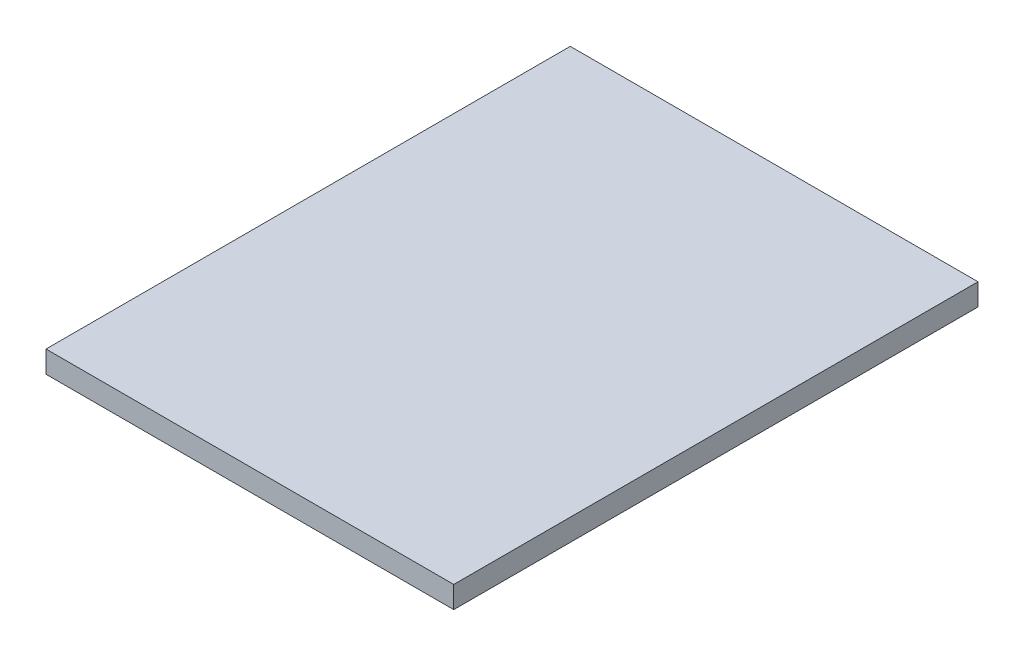
SolidWorks part; units mm, degrees
material "Acrylic (Medium-high impact)"
ref_plane "Front Plane" through (0, 0, 0) normal (0, 0, 1) x (1, 0, 0)
ref_plane "Top Plane" through (0, 0, 0) normal (0, 1, 0) x (1, 0, 0)
ref_plane "Right Plane" through (0, 0, 0) normal (1, 0, 0) x (0, 0, -1)
sketch "Sketch1" plane through (0, 0, 0) normal (0, 1, 0) x (1, 0, 0)
  line L1 (-88.9, 114.3) -> (88.9, 114.3)
  line L2 (-88.9, 114.3) -> (-88.9, -114.3)
  line L3 (-88.9, -114.3) -> (88.9, -114.3)
  line L4 (88.9, 114.3) -> (88.9, -114.3)
  line L5 (-88.9, 114.3) -> (88.9, -114.3) construction
  line L6 (-88.9, -114.3) -> (88.9, 114.3) construction
  point P0 (0, 0)
  dimension "D1" = 177.8
  dimension "D2" = 228.6
extrude "Boss-Extrude1" add sketch "Sketch1" along normal blind 9.525
